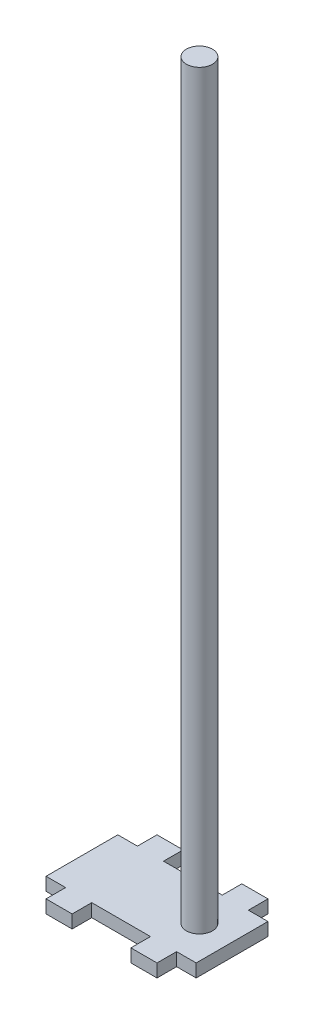
SolidWorks part; units mm, degrees
ref_plane "Plano frontal" through (0, 0, 0) normal (0, 0, 1) x (1, 0, 0)
ref_plane "Plano superior" through (0, 0, 0) normal (0, 1, 0) x (1, 0, 0)
ref_plane "Plano direito" through (0, 0, 0) normal (1, 0, 0) x (0, 0, -1)
sketch "Sketch1" plane through (0, 0, 0) normal (0, 1, 0) x (1, 0, 0)
  line L1 (-11.5, 5.5) -> (11.5, 5.5)
  line L2 (-11.5, 5.5) -> (-11.5, -5.5)
  line L3 (-11.5, -5.5) -> (11.5, -5.5)
  line L4 (11.5, 5.5) -> (11.5, -5.5)
  point P4 (0, 5.5)
  point P6 (-11.5, 0)
  dimension "D1" = 23
  dimension "D2" = 11
extrude "Boss-Extrude1" add sketch "Sketch1" along normal mid plane 2
sketch "Sketch3" plane through (0, 0, 0) normal (0, 1, 0) x (1, 0, 0)
  line L0 (11.5, 5.5) -> (-11.5, 5.5) construction
  line L1 (4.5, 5.5) -> (8.5, 5.5)
  line L2 (4.5, 5.5) -> (4.5, 8.5)
  line L3 (4.5, 8.5) -> (8.5, 8.5)
  line L4 (8.5, 5.5) -> (8.5, 8.5)
  line L6 (11.5, -5.5) -> (11.5, 5.5) construction
  line L7 (-12.65, 0) -> (12.65, 0) construction
  line L8 (8.5, -5.5) -> (8.5, -8.5)
  line L9 (4.5, -8.5) -> (8.5, -8.5)
  line L10 (4.5, -5.5) -> (4.5, -8.5)
  line L11 (4.5, -5.5) -> (8.5, -5.5)
  line L12 (0, -9.35) -> (0, 9.35) construction
  line L13 (-4.5, -5.5) -> (-8.5, -5.5)
  line L14 (-4.5, -5.5) -> (-4.5, -8.5)
  line L15 (-4.5, -8.5) -> (-8.5, -8.5)
  line L16 (-8.5, -5.5) -> (-8.5, -8.5)
  line L17 (-8.5, 5.5) -> (-8.5, 8.5)
  line L18 (-4.5, 8.5) -> (-8.5, 8.5)
  line L19 (-4.5, 5.5) -> (-4.5, 8.5)
  line L20 (-4.5, 5.5) -> (-8.5, 5.5)
  dimension "D1" = 3
  dimension "D3" = 3
  dimension "D4" = 4
extrude "Boss-Extrude3" add sketch "Sketch3" along normal mid plane 2
sketch "Sketch2" plane through (0, 1, 0) normal (0, 1, 0) x (1, 0, 0)
  line L6 (6.5, 8.5) -> (6.5, -8.5) construction
  line L7 (8.5, 8.5) -> (4.5, 8.5) construction
  line L8 (4.5, -8.5) -> (8.5, -8.5) construction
  circle A1 centre (6.5, 0) radius 2
  dimension "D1" = 4
extrude "Boss-Extrude2" add sketch "Sketch2" along normal blind 115
